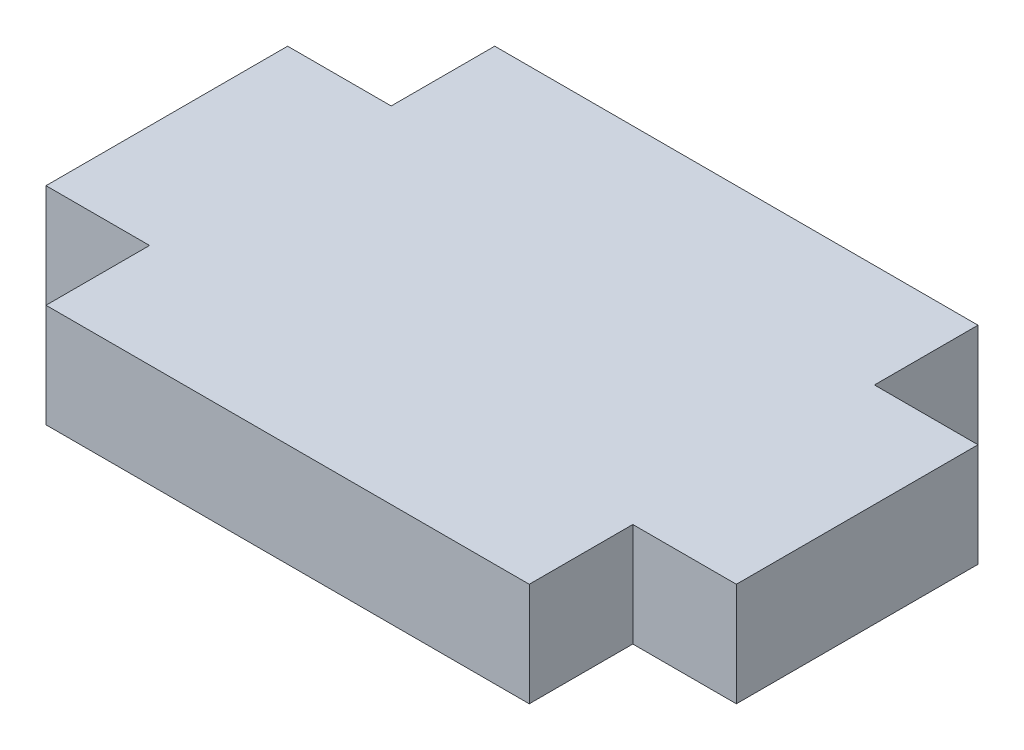
SolidWorks part; units mm, degrees
ref_plane "Alzado" through (0, 0, 0) normal (0, 0, 1) x (1, 0, 0)
ref_plane "Planta" through (0, 0, 0) normal (0, 1, 0) x (1, 0, 0)
ref_plane "Vista lateral" through (0, 0, 0) normal (1, 0, 0) x (0, 0, -1)
sketch "Croquis1" plane through (0, 0, 0) normal (0, 1, 0) x (1, 0, 0)
  line L0 (0, 0) -> (0, 7)
  line L1 (0, 7) -> (3, 7)
  line L2 (20, 7) -> (20, 0)
  line L3 (20, 0) -> (17, 0)
  line L4 (3, 0) -> (0, 0)
  line L5 (3, 10) -> (17, 10)
  line L6 (17, 10) -> (17, 7)
  line L7 (3, 10) -> (3, 7)
  line L9 (3, -3) -> (3, 0)
  line L10 (17, -3) -> (17, 0)
  line L11 (3, -3) -> (17, -3)
  line L13 (17, 7) -> (20, 7)
  dimension "D1" = 7
  dimension "D2" = 20
extrude "Saliente-Extruir1" add sketch "Croquis1" along normal blind 3
